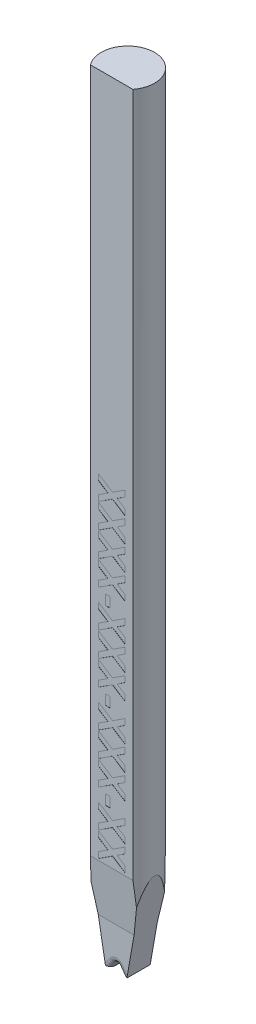
SolidWorks part; units mm, degrees
ref_plane "Ebene vorne" through (0, 0, 0) normal (0, 0, 1) x (1, 0, 0)
ref_plane "Ebene oben" through (0, 0, 0) normal (0, 1, 0) x (1, 0, 0)
ref_plane "Ebene rechts" through (0, 0, 0) normal (1, 0, 0) x (0, 0, -1)
sketch "sketch_TL_cutting" plane through (0, 0, 0) normal (0, 1, 0) x (1, 0, 0)
  circle A0 centre (0, 0) radius 0.9969
extrude "TL_cutting" add sketch "sketch_TL_cutting" along normal blind 29.0068
sketch "sketch_TDF_grinding" plane through (0, 0, 0) normal (0, 1, 0) x (1, 0, 0)
  line L0 (0, 0) -> (0, -0.6033) construction
  line L1 (-1.007, -2.6171) -> (1.007, -2.6171)
  line L2 (-1.007, -2.6171) -> (-1.007, -0.6033)
  line L3 (-1.007, -0.6033) -> (1.007, -0.6032)
  line L4 (1.007, -2.6171) -> (1.007, -0.6032)
  circle A1 centre (0, 0) radius 0.9969 construction
  point P9 (0, -2.6172)
  dimension "TD_2Offset_X" = 2.0139
  dimension "TD_2Offset_Z" = 2.0139
extrude "TDF_grinding" cut sketch "sketch_TDF_grinding" along normal through all
sketch "sketch_engraving" plane through (0, 0, 0.6033) normal (0, 0, 1) x (1, 0, 0)
  line L0 (0.7937, 29.0068) -> (-0.7937, 29.0068) construction
  line L6 (-0.7937, 0) -> (0.7937, 0) construction
  line L7 (0, 0) -> (0, 15.9537) construction
  line L8 (-0.5, 15.9537) -> (-0.5, 0) construction
  text T0 "XXXX-XXX-XXX-XX" font "Arial" height 1
  dimension "D2" = 0.5
  dimension "EngravingStart" = 13.0531
extrude "engraving" cut sketch "sketch_engraving" against normal blind 0.005
sketch "sketch_VW_VR_grinding" plane through (0, 0, 0) normal (0, 0, 1) x (1, 0, 0)
  line L0 (-0.9919, -0.01) -> (-0.9919, 1.509)
  line L1 (0.9919, -0.01) -> (0.9919, 1.509)
  line L2 (-0.9919, 0) -> (0.9919, 0) construction
  line L3 (-1.007, 1.514) -> (-0.9969, 1.514)
  line L4 (0.9969, 1.514) -> (1.007, 1.514)
  line L5 (-1.007, 1.514) -> (-1.007, -0.01)
  line L6 (-1.007, -0.01) -> (-0.9919, -0.01)
  line L7 (0.9919, -0.01) -> (1.007, -0.01)
  line L8 (1.007, -0.01) -> (1.007, 1.514)
  line L9 (-0.9969, 1.514) -> (-0.9969, 1.509) construction
  line L10 (-0.9919, 1.509) -> (-0.9969, 1.509) construction
  line L11 (0.9919, 1.509) -> (0.9969, 1.509) construction
  line L12 (0.9969, 1.514) -> (0.9969, 1.509) construction
  arc A0 (-0.9969, 1.514) -> (-0.9919, 1.509) centre (-0.9969, 1.509) cw
  arc A2 (0.9919, 1.509) -> (0.9969, 1.514) centre (0.9969, 1.509) cw
  dimension "D1" = 0.01
  dimension "D4" = 2.0139
extrude "VW_VR_grinding" cut sketch "sketch_VW_VR_grinding" against normal blind 1.007 and the other way blind 1.007
sketch "sketch_ISA_grinding" plane through (0, 0, 0) normal (0, 0, 1) x (1, 0, 0)
  line L0 (-0.4001, 0) -> (-1.007, 3.4419)
  line L4 (1.007, 3.4419) -> (0.4001, 0)
  line L5 (0.4001, 0) -> (-0.4001, 0)
  line L6 (0, 0) -> (0, 30.49) construction
  line L7 (-1.007, 3.4419) -> (-1.007, -0.01)
  line L12 (-1.007, -0.01) -> (1.007, -0.01)
  line L13 (1.007, -0.01) -> (1.007, 3.4419)
  dimension "ISA" = 20
  dimension "TD_2Offset" = 2.0139
  dimension "Offset" = 0.01
extrude "ISA_grinding" cut sketch "sketch_ISA_grinding" against normal blind 1.007 and the other way blind 1.007
sketch "sketch_pre_FRX_BRX" plane through (0, 0, 0) normal (1, 0, 0) x (0, 0, -1)
  line L0 (0.9969, -0.01) -> (0.9969, 3.9152) construction
  line L1 (-0.6033, -0.01) -> (-0.6033, 1.514) construction
  line L2 (-0.4356, -0.01) -> (-0.4356, 1.514)
  line L3 (-0.4356, 1.514) -> (-1.007, 1.514)
  line L4 (-1.007, 1.514) -> (-1.007, -0.01)
  line L5 (-1.007, -0.01) -> (-0.4356, -0.01)
  line L6 (0.4356, -0.01) -> (0.4356, 1.514)
  line L7 (0.4356, 1.514) -> (1.0069, 1.514)
  line L8 (1.0069, 1.514) -> (1.007, -0.01)
  line L9 (1.007, -0.01) -> (0.4356, -0.01)
  dimension "D3" = 0.01
  dimension "D4" = 1.524
  dimension "D5" = 2.0139
  dimension "D6" = 0.8712
  dimension "D2" = 0.01
  dimension "D7" = 1.4326
extrude "pre_FRX_BRX" cut sketch "sketch_pre_FRX_BRX" against normal blind 1.007 and the other way blind 1.007
sketch "sketch_contour_V-Groove" plane through (0, 0, 0) normal (1, 0, 0) x (0, 0, -1)
  line L0 (-0.6033, 0.254) -> (0, 0.254)
  line L1 (0, 0.254) -> (0.9969, 0.254)
  line L2 (0.9969, -0.8411) -> (0.9969, 1.3178) construction
  line L3 (-0.6033, -0.9209) -> (-0.6033, 1.9363) construction
  line L4 (-0.6033, 0) -> (0.997, 0) construction
  line L5 (0.4356, 0) -> (0.4356, 0.254) construction
  line L6 (-0.4356, 0) -> (-0.4356, 0.254) construction
  dimension "D1" = 0
ref_plane "front" through (0, 0, 0.6033) normal (0, 0, 1) x (1, 0, 0)
ref_plane "back" through (0, 0, -0.9969) normal (0, 0, 1) x (1, 0, 0)
sketch "sketch_section_V-Groove" plane through (0, 0, 0.6033) normal (0, 0, 1) x (1, 0, 0)
  line L0 (-1.9982, -2.54) -> (-0.0659, 0.2197)
  line L2 (0.0659, 0.2197) -> (1.9982, -2.54)
  line L3 (-1.9982, -2.54) -> (1.9982, -2.54)
  line L4 (0, -2.54) -> (0, 0.254) construction
  line L5 (-0.2197, 0) -> (0.2197, 0) construction
  arc A0 (0.0659, 0.2197) -> (-0.0659, 0.2197) centre (0, 0.1736) ccw
  dimension "GA" = 70
sweep "V-Groove_EDM" cut profiles "sketch_section_V-Groove" path "sketch_contour_V-Groove"
fillet "FR_EDM" radius 0.2007 3 edges at (0.1428, 0.1099, 0.4356) (0, 0.254, 0.4356) (-0.1428, 0.1099, 0.4356)
fillet "BR_EDM" radius 0.2007 3 edges at (0.1428, 0.1099, -0.4356) (0, 0.254, -0.4356) (-0.1428, 0.1099, -0.4356)
sketch "sketch_FA_BA_grinding" plane through (0, 0, 0) normal (1, 0, 0) x (0, 0, -1)
  line L2 (1.9969, 19.3702) -> (1.997, -0.1)
  line L3 (1.997, -0.1) -> (0.4356, -0.1)
  line L5 (0.4356, -0.1) -> (0.4356, 1.524)
  line L6 (0.4356, 1.524) -> (1.9969, 19.3702)
  line L7 (0.9969, -0.1) -> (0.9969, 7.9401) construction
  line L8 (-0.6032, 3.4401) -> (-0.6032, -0.1) construction
  line L9 (-2.2816, 22.6236) -> (-0.4356, 1.524)
  line L10 (-0.4356, 1.524) -> (-0.4356, -0.1)
  line L11 (-0.4356, -0.1) -> (-2.2816, -0.1)
  line L12 (-2.2816, -0.1) -> (-2.2816, 22.6236)
  line L13 (-0.4356, 1.524) -> (0.4356, 1.524) construction
  dimension "D4" = 1
  dimension "D1" = 0.1
  dimension "FA" = 5
  dimension "BA" = 5
extrude "FA_BA_grinding" cut sketch "sketch_FA_BA_grinding" against normal blind 1.007 and the other way blind 1.007
sketch "sketch_groove_dimensions" plane through (0, 0, 0) normal (1, 0, 0) x (0, 0, -1)
  line L0 (-0.235, 0.254) -> (0.235, 0.254)
  line L1 (-0.4356, 0) -> (-0.4356, 0.4547) construction
  line L2 (0.9969, 0) -> (0.9969, 0.4166) construction
  line L3 (0.4356, 0) -> (0.4356, 0.4547) construction
  line L4 (-0.6033, 0) -> (-0.6033, 0.3999) construction
  arc A0 (0.235, 0.254) -> (0.4356, 0.4547) centre (0.235, 0.4547) ccw
  arc A1 (-0.235, 0.254) -> (-0.4356, 0.4547) centre (-0.235, 0.4547) cw
equation "\"_Offset\"=0.01mm"
equation "\"TL\"=29.0068mm"
equation "\"TD\"=1.9939mm"
equation "\"TDF\"=1.6002mm"
equation "\"BA\"=5deg"
equation "\"ISA\"=20deg"
equation "\"FA\"=5deg"
equation "\"GR\"=0.08128mm"
equation "\"GA\"=70deg"
equation "\"GD\"=0.254mm"
equation "\"FL\"=0.87122mm"
equation "\"F\"=0.4699mm"
equation "\"FX\"=0.16764mm"
equation "\"B\"=0.43942mm"
equation "\"VW\"=0mm"
equation "\"cleaned_VR\"= IIF ( \"VR\" > 0 , \"VR\" , \"E\" - \"_Offset\" )"
equation "\"cleaned_VW\"= IIF ( \"VW\" > 0 , \"VW\" , \"TD\" - \"_Offset\" )"
equation "\"back_edge\"= \"TD\" / 2 - \"X\""
equation "\"side_edge_Offset\"= \"TD\" / 2 + \"_Offset\""
equation "\"TD@sketch_TL_cutting\"=\"TD\""
equation "\"TL@TL_cutting\"=\"TL\""
equation "\"TDF@sketch_TDF_grinding\"=\"TDF\""
equation "\"TD_2Offset_X@sketch_TDF_grinding\"=\"TD\"+2*\"_Offset\""
equation "\"TD_2Offset_Z@sketch_TDF_grinding\"=\"TD\"+2*\"_Offset\""
equation "\"TL_Offset\"= \"TL\" + \"_Offset\""
equation "\"ISA@sketch_ISA_grinding\"=\"ISA\""
equation "\"W@sketch_ISA_grinding\"=\"W\""
equation "\"TD_2Offset@sketch_ISA_grinding\"=\"TD\"+2*\"_Offset\""
equation "\"Offset@sketch_ISA_grinding\"=\"_Offset\""
equation "\"05TD_Offset_posZ@ISA_grinding\"=\"side_edge_Offset\""
equation "\"05TD_Offset_negZ@ISA_grinding\"=\"side_edge_Offset\""
equation "\"E\"=1.524mm"
equation "\"cleaned_X\"= IIF ( \"X\" > 0 , \"X\" , \"TD\" / 2 - \"FL\" / 2 )"
equation "\"FR\"=0.20066mm"
equation "\"BR\"=0.20066mm"
equation "\"D1\"= \"side_edge_Offset\""
equation "\"D2\"= \"side_edge_Offset\""
equation "\"TDF@sketch_FA_BA_grinding\" = \"TDF\""
equation "\"FL@sketch_FA_BA_grinding\"=\"FL\""
equation "\"E@sketch_FA_BA_grinding\" = \"E\""
equation "\"D1@FA_BA_grinding\"=\"side_edge_Offset\""
equation "\"D2@FA_BA_grinding\"=\"side_angle_Offset\""
equation "\"10GD@sketch_section_V-Groove\" = 10 * \"GD\""
equation "\"GA@sketch_section_V-Groove\" = \"GA\""
equation "\"GD@sketch_section_V-Groove\" = \"GD\""
equation "\"B@sketch_section_V-Groove\" = \"B\""
equation "\"GD@sketch_contour_V-Groove\" = \"GD\""
equation "\"cleaned_FRX\"= IIF ( \"FRX\" > 0 , \"FRX\" , \"FR\" )"
equation "\"cleaned_BRX\"= IIF ( \"BRX\" > 0 , \"BRX\" , \"BR\" )"
equation "\"FL_groove_angle\"=0deg"
equation "\"D3@sketch_pre_FRX_BRX\" = \"_Offset\""
equation "\"D4@sketch_pre_FRX_BRX\" = \"E\""
equation "\"D5@sketch_pre_FRX_BRX\" = 2 * \"side_edge_Offset\""
equation "\"D6@sketch_pre_FRX_BRX\" = \"FL\" + ( \"FR\" - \"cleaned_FRX\" ) + ( \"BR\" - \"cleaned_BRX\" )"
equation "\"TD/2@sketch_pre_FRX_BRX\" = \"TD\" / 2"
equation "\"TDF@sketch_pre_FRX_BRX\" = \"TDF\""
equation "\"D2@sketch_pre_FRX_BRX\" = \"_Offset\""
equation "\"D1@pre_FRX_BRX\" = \"side_edge_Offset\""
equation "\"D2@pre_FRX_BRX\" = \"side_edge_Offset\""
equation "\"D1@BR_EDM\"=\"BR\""
equation "\"TD/2@sketch_FA_BA_grinding\" = \"TD\" / 2"
equation "\"TD/2@sketch_contour_V-Groove\" = \"TD\" / 2"
equation "\"TDF@sketch_contour_V-Groove\" = \"TDF\""
equation "\"D1@sketch_contour_V-Groove\"=\"FL_groove_angle\""
equation "\"FL@sketch_contour_V-Groove\"=\"FL\""
equation "\"FL/2@sketch_contour_V-Groove\" = \"FL\" / 2"
equation "\"D1@FR_EDM\"=\"FR\""
equation "\"D1@sketch_VW_VR_grinding\" = \"_Offset\""
equation "\"D4@sketch_VW_VR_grinding\" = 2 * \"side_edge_Offset\""
equation "\"VR@sketch_VW_VR_grinding\" = \"cleaned_VR\""
equation "\"VW@sketch_VW_VR_grinding\"=\"cleaned_VW\""
equation "\"D1@VW_VR_grinding\" = \"side_edge_Offset\""
equation "\"D2@VW_VR_grinding\" = \"side_edge_Offset\""
equation "\"X\"=0mm"
equation "\"VR\"=0mm"
equation "\"W\"=0.8001mm"
equation "\"VW_radius\"= \"cleaned_VW\" / 10"
equation "\"VW_radius_cleaned\"= IIF ( \"VW\" > 0 , \"VW_radius\" , \"_Offset\" / 2 )"
equation "\"D2@sketch_VW_VR_grinding\"=\"VW_radius_cleaned\""
equation "\"FRX\"=0mm"
equation "\"BRX\"=0mm"
equation "\"FA@sketch_FA_BA_grinding\" = \"FA\""
equation "\"D4@sketch_FA_BA_grinding\"=\"_Offset\"*100"
equation "\"BA@sketch_FA_BA_grinding\" = \"BA\""
equation "\"D1@sketch_groove_dimensions\" = \"TD\" / 2"
equation "\"FL@sketch_groove_dimensions\" = \"FL\""
equation "\"FR@sketch_groove_dimensions\" = \"FR\""
equation "\"BR@sketch_groove_dimensions\" = \"BR\""
equation "\"FRX@sketch_groove_dimensions\" = \"cleaned_FRX\""
equation "\"BRX@sketch_groove_dimensions\" = \"cleaned_BRX\""
equation "\"GD@sketch_groove_dimensions\" = \"GD\""
equation "\"cleaned_FX\"= IIF ( \"FX\" > 0 , \"FX\" , \"TDF\" - ( \"TD\" + \"FL\" ) / 2 )"
equation "\"D7@sketch_pre_FRX_BRX\"=\"TDF\"-\"cleaned_FX\"-(\"FR\"-\"cleaned_FRX\")"
equation "\"FX@sketch_contour_V-Groove\" = \"cleaned_FX\""
equation "\"FX@sketch_FA_BA_grinding\" = \"cleaned_FX\""
equation "\"TDF@sketch_groove_dimensions\" = \"TDF\""
equation "\"FX@sketch_groove_dimensions\" = \"cleaned_FX\""
equation "\"EngravingStart\" = \"TL\" * 0.45"
equation "\"EngravingStart@sketch_engraving\" = \"EngravingStart\""
